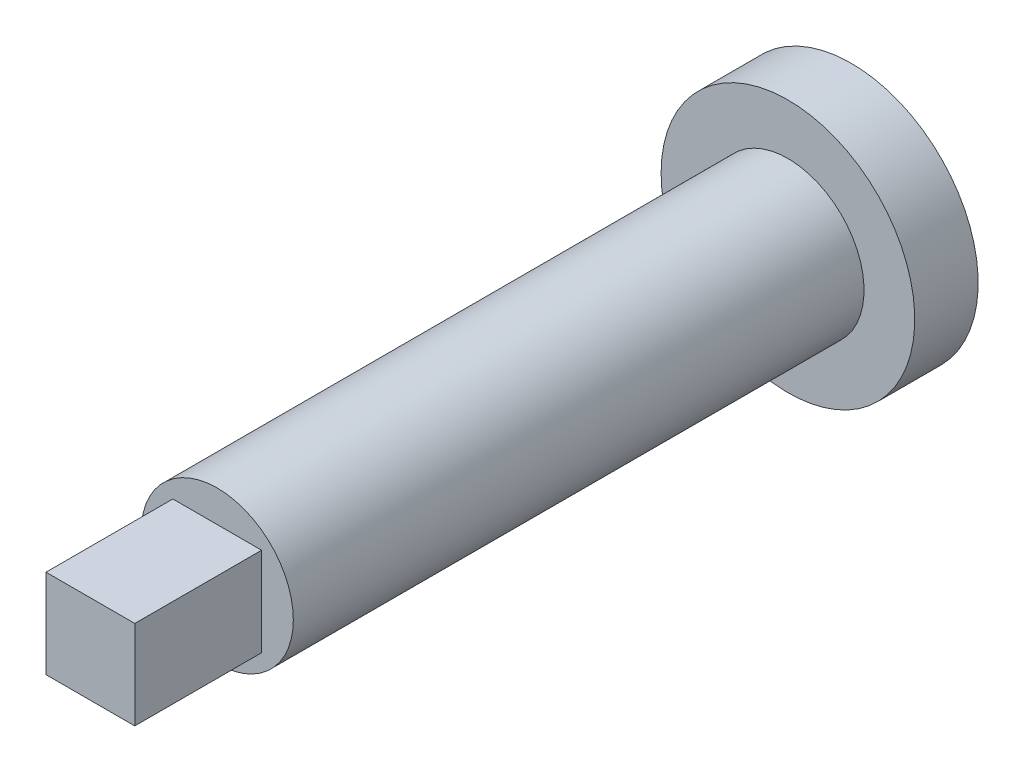
SolidWorks part; units mm, degrees
ref_plane "Front Plane" through (0, 0, 0) normal (0, 0, 1) x (1, 0, 0)
ref_plane "Top Plane" through (0, 0, 0) normal (0, 1, 0) x (1, 0, 0)
ref_plane "Right Plane" through (0, 0, 0) normal (1, 0, 0) x (0, 0, -1)
sketch "Sketch1" plane through (0, 0, 0) normal (0, 0, 1) x (1, 0, 0)
  circle A0 centre (0, 0) radius 6
  dimension "D1" = 12
extrude "Boss-Extrude1" add sketch "Sketch1" along normal blind 50
sketch "Sketch2" plane through (0, 0, 0) normal (0, 0, -1) x (-1, 0, 0)
  circle A0 centre (0, 0) radius 10
  dimension "D1" = 20
extrude "Boss-Extrude2" add sketch "Sketch2" against normal blind 5
sketch "Sketch3" plane through (0, 0, 50) normal (0, 0, 1) x (1, 0, 0)
  line L1 (-3.5, -3.5) -> (3.5, -3.5)
  line L2 (-3.5, -3.5) -> (-3.5, 3.5)
  line L3 (-3.5, 3.5) -> (3.5, 3.5)
  line L4 (3.5, -3.5) -> (3.5, 3.5)
  line L5 (-3.5, -3.5) -> (3.5, 3.5) construction
  line L6 (-3.5, 3.5) -> (3.5, -3.5) construction
  point P0 (0, 0)
  dimension "D1" = 7
  dimension "D2" = 7
extrude "Boss-Extrude3" add sketch "Sketch3" along normal blind 10
